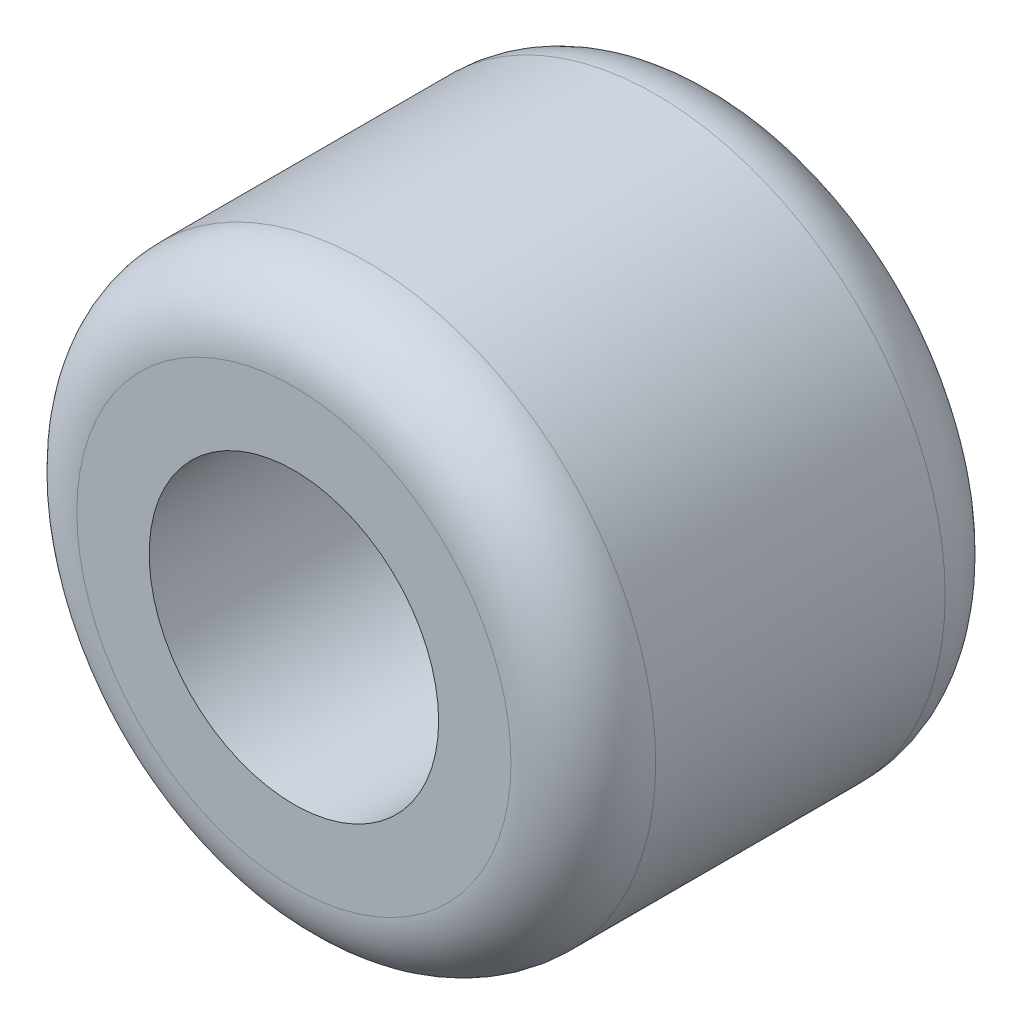
SolidWorks part; units mm, degrees
ref_plane "Front" through (0, 0, 0) normal (0, 0, 1) x (1, 0, 0)
ref_plane "Top" through (0, 0, 0) normal (0, 1, 0) x (1, 0, 0)
ref_plane "Right" through (0, 0, 0) normal (1, 0, 0) x (0, 0, -1)
sketch "草图1" plane through (0, 0, 0) normal (0, 0, 1) x (1, 0, 0)
  circle A0 centre (0, 0) radius 2
  circle A1 centre (0, 0) radius 4
  dimension "D1" = 4
  dimension "D2" = 8
extrude "凸台-拉伸1" add sketch "草图1" along normal blind 6
fillet "圆角1" radius 1 1 edges at (4, 0, 6)
fillet "圆角2" radius 1 1 edges at (4, 0, 0)
